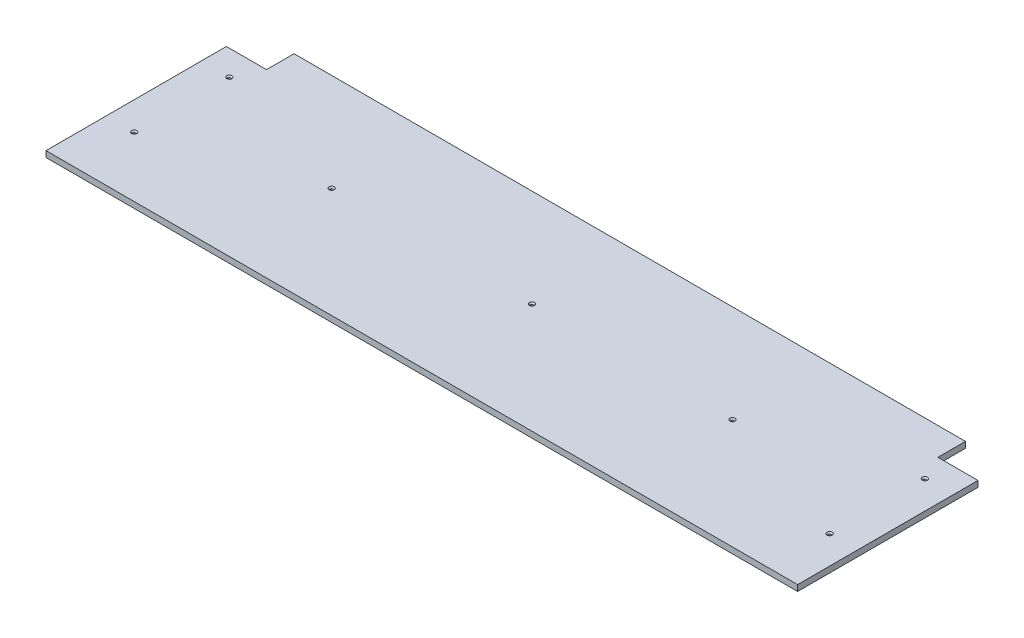
SolidWorks part; units mm, degrees
ref_plane "Front Plane" through (0, 0, 0) normal (0, 0, 1) x (1, 0, 0)
ref_plane "Top Plane" through (0, 0, 0) normal (0, 1, 0) x (1, 0, 0)
ref_plane "Right Plane" through (0, 0, 0) normal (1, 0, 0) x (0, 0, -1)
sketch "Sketch1" plane through (0, 0, 0) normal (0, 1, 0) x (1, 0, 0)
  line L1 (750, -207.5) -> (-750, -207.5)
  line L2 (750, -207.5) -> (750, 207.5)
  line L3 (750, 207.5) -> (-750, 207.5)
  line L4 (-750, -207.5) -> (-750, 207.5)
  line L5 (750, -207.5) -> (-750, 207.5) construction
  line L6 (750, 207.5) -> (-750, -207.5) construction
  point P0 (0, 0)
  dimension "D1" = 1500
  dimension "D2" = 415
extrude "RawMaterial" add sketch "Sketch1" along normal blind 12
hole_wizard "CSK for M5 Flat Head Machine Screw1" positions "Sketch3" profile "Sketch4" countersink size "M5" standard "ANSI Metric" end condition through all
sketch "Sketch3" plane through (0, 12, 0) normal (0, -1, 0) x (-1, 0, 0)
  line L6 (-750, -207.5) -> (-750, 207.5) construction
  line L7 (-750, 207.5) -> (750, 207.5) construction
  point P0 (-694, 102.5)
  point P2 (-694, -87.5)
  point P4 (-400, 12.5)
  point P6 (400, 12.5)
  point P8 (694, -87.5)
  point P10 (694, 102.5)
  point P50 (0, 12.5)
  dimension "D1" = 190
  dimension "D2" = 295
  dimension "D3" = 100
  dimension "D4" = 800
  dimension "D5" = 350
  dimension "D6" = 56
  dimension "D7" = 1444
sketch "Sketch4" plane through (694, 12, -102.5) normal (1, 0, 0) x (0, 0, 1)
  line L0 (0, 0) -> (0, 12)
  line L1 (0, 12) -> (2.6, 12)
  line L2 (2.6, 12) -> (2.6, 2.6)
  line L3 (2.6, 2.6) -> (5.2, 0)
  line L5 (5.2, 0) -> (0, 0)
  line L6 (-2.6, 2.6) -> (-5.2, 0) construction
  line L11 (0, -6.35) -> (0, 107.95) construction
  dimension "Thru Hole Dia." = 5.2
  dimension "Thru Hole Depth" = 12
  dimension "Near C'Sink Dia." = 10.4
  dimension "Near C'Sink Angle" = 90
sketch "Sketch5" plane through (0, 0, 0) normal (0, -1, 0) x (1, 0, 0)
  line L0 (-750, -152.5) -> (-670, -152.5)
  line L1 (-750, -207.5) -> (-750, 207.5) construction
  line L2 (670, -152.5) -> (670, -207.5)
  line L4 (750, -152.5) -> (670, -152.5)
  line L5 (750, 207.5) -> (750, -207.5) construction
  line L6 (750, -207.5) -> (-750, -207.5) construction
  line L7 (-670, -152.5) -> (-670, -207.5)
  line M10 (-750, 207.5) -> (-750, -207.5)
  line M11 (-750, -207.5) -> (750, -207.5)
  line M12 (750, -207.5) -> (750, 207.5)
  dimension "D1" = 80
  dimension "D2" = 55
extrude "Frame Slots" cut sketch "Sketch5" against normal through all contours L7 L0 M10 M11 | L4 L2 M12 M11
